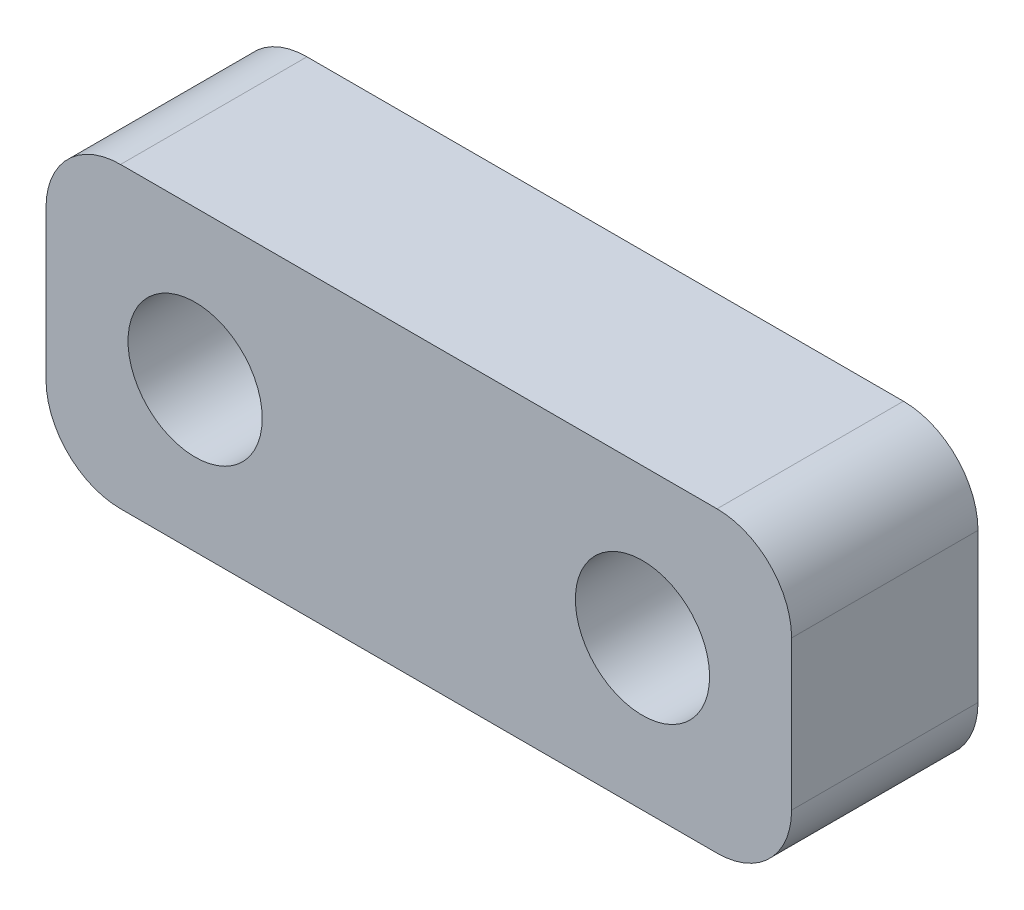
SolidWorks part; units mm, degrees
ref_plane "Front Plane" through (0, 0, 0) normal (0, 0, 1) x (1, 0, 0)
ref_plane "Top Plane" through (0, 0, 0) normal (0, 1, 0) x (1, 0, 0)
ref_plane "Right Plane" through (0, 0, 0) normal (1, 0, 0) x (0, 0, -1)
sketch "Sketch2" plane through (0, 0, 0) normal (0, 0, 1) x (1, 0, 0)
  line L1 (0, 0) -> (20, 0)
  line L2 (0, 0) -> (0, 8)
  line L3 (0, 8) -> (20, 8)
  line L4 (20, 0) -> (20, 8)
  dimension "D1" = 20
  dimension "D2" = 8
extrude "Boss-Extrude1" add sketch "Sketch2" along normal blind 5
sketch "Sketch4" plane through (0, 0, 5) normal (0, 0, 1) x (1, 0, 0)
  line L0 (0, 4) -> (20, 4) construction
  line L1 (0, 8) -> (0, 0) construction
  line L2 (20, 0) -> (20, 8) construction
  line L3 (10, 8) -> (10, 0) construction
  line L4 (20, 8) -> (0, 8) construction
  line L5 (0, 0) -> (20, 0) construction
  point P12 (4, 4)
  point P13 (16, 4)
  dimension "D1" = 12
hole_wizard "M3 Clearance Hole1" positions "Sketch6" profile "Sketch5" hole size "M3" standard "ANSI Metric" end condition through all
sketch "Sketch6" plane through (0, 0, 5) normal (0, 0, 1) x (1, 0, 0)
  point P0 (4, 4)
  point P3 (16, 4)
sketch "Sketch5" plane through (4, 4, 5) normal (1, 0, 0) x (0, -1, 0)
  line L0 (0, 0) -> (0, 5)
  line L1 (0, 5) -> (1.8, 5)
  line L2 (1.8, 5) -> (1.8, 0)
  line L5 (1.8, 0) -> (0, 0)
  line L11 (0, -6.35) -> (0, 107.95) construction
  dimension "Thru Hole Dia." = 3.6
  dimension "Thru Hole Depth" = 5
fillet "Fillet1" radius 2 4 edges at (0, 0, 2.5) (20, 0, 2.5) (20, 8, 2.5) (0, 8, 2.5)
